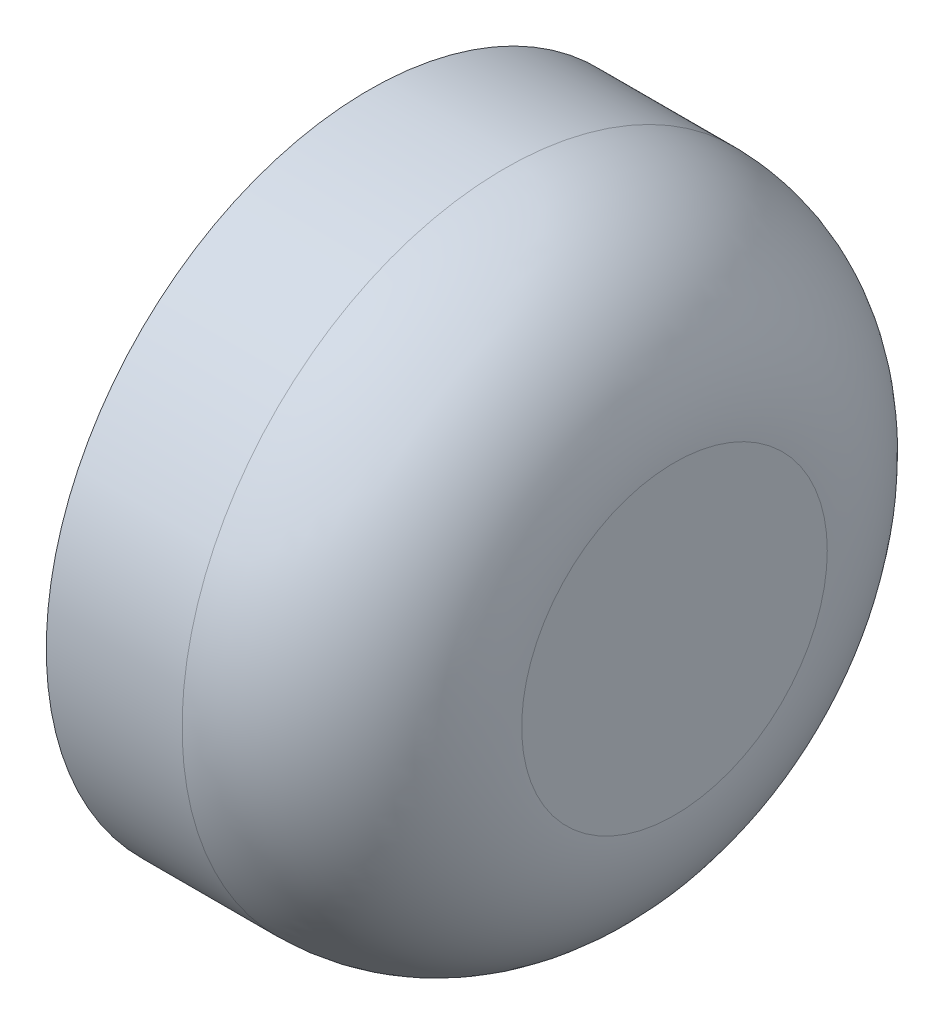
SolidWorks part; units mm, degrees
ref_plane "Front Plane" through (0, 0, 0) normal (0, 0, 1) x (1, 0, 0)
ref_plane "Top Plane" through (0, 0, 0) normal (0, 1, 0) x (1, 0, 0)
ref_plane "Right Plane" through (0, 0, 0) normal (1, 0, 0) x (0, 0, -1)
sketch "Sketch2" plane through (0, -0.009, 0.0001) normal (1, 0, 0) x (0, 0, -1)
  circle A0 centre (0.1074, 0.0375) radius 4.75
  dimension "D1" = 9.5
extrude "Boss-Extrude1" add sketch "Sketch2" along normal blind 4.5
fillet "Fillet1" radius 2.5 1 edges at (4.5, 0.0284, -4.8573)
sketch "Sketch4" plane through (0, 0, 0) normal (-1, 0, 0) x (0, 0, 1)
  circle A0 centre (0, 0) radius 3.3
  dimension "D1" = 6.6
extrude "Cut-Extrude1" cut sketch "Sketch4" against normal blind 1
